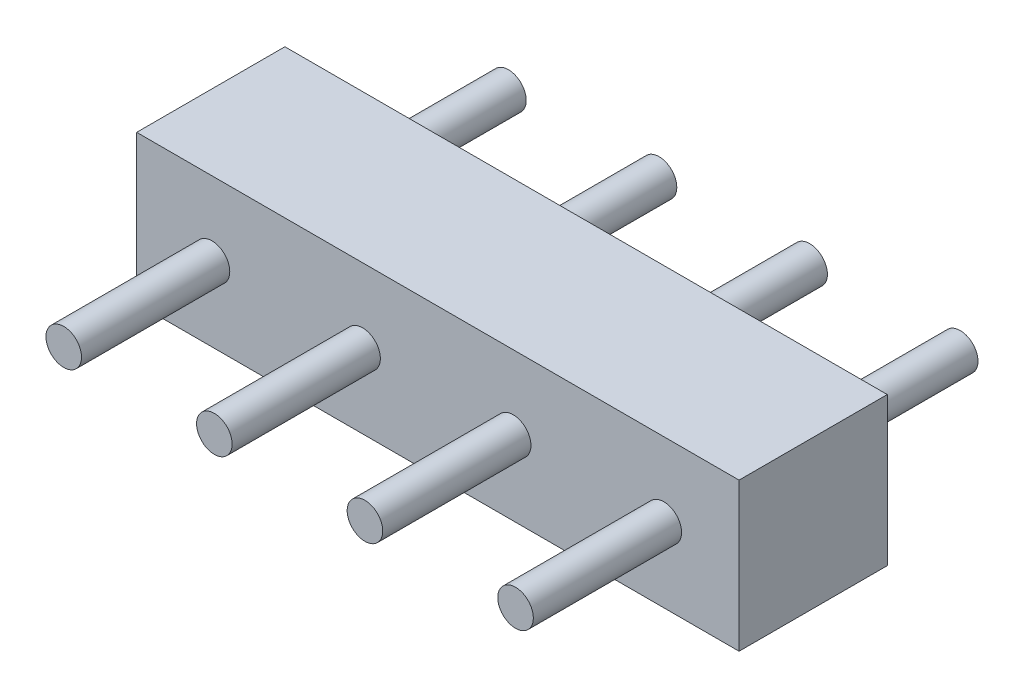
SolidWorks part; units mm, degrees
ref_plane "前视基准面" through (0, 0, 0) normal (0, 0, 1) x (1, 0, 0)
ref_plane "上视基准面" through (0, 0, 0) normal (0, 1, 0) x (1, 0, 0)
ref_plane "右视基准面" through (0, 0, 0) normal (1, 0, 0) x (0, 0, -1)
sketch "草图1" plane through (0, 0, 0) normal (0, 0, 1) x (1, 0, 0)
  line L1 (0, 0) -> (10.16, 0)
  line L2 (0, 0) -> (0, 2.5)
  line L3 (0, 2.5) -> (10.16, 2.5)
  line L4 (10.16, 0) -> (10.16, 2.5)
  dimension "D1" = 2.5
  dimension "D2" = 10.16
extrude "凸台-拉伸1" add sketch "草图1" along normal blind 2.5
sketch "草图2" plane through (0, 0, 2.5) normal (0, 0, 1) x (1, 0, 0)
  line L0 (5.08, 2.5) -> (5.08, -1.7995) construction
  line L1 (10.16, 2.5) -> (0, 2.5) construction
  line L2 (0, 1.25) -> (15.9024, 1.25) construction
  line L3 (0, 2.5) -> (0, 0) construction
  circle A0 centre (3.81, 1.25) radius 0.3
  dimension "D1" = 1.27
  dimension "D2" = 0.6
extrude "凸台-拉伸2" add sketch "草图2" along normal blind 2.5 and the other way blind 5
pattern_linear "阵列(线性)1" count 3 spacing 2.54 along (1, 0, 0) count 2 spacing 2.54 along (-1, 0, 0) of "凸台-拉伸2"
